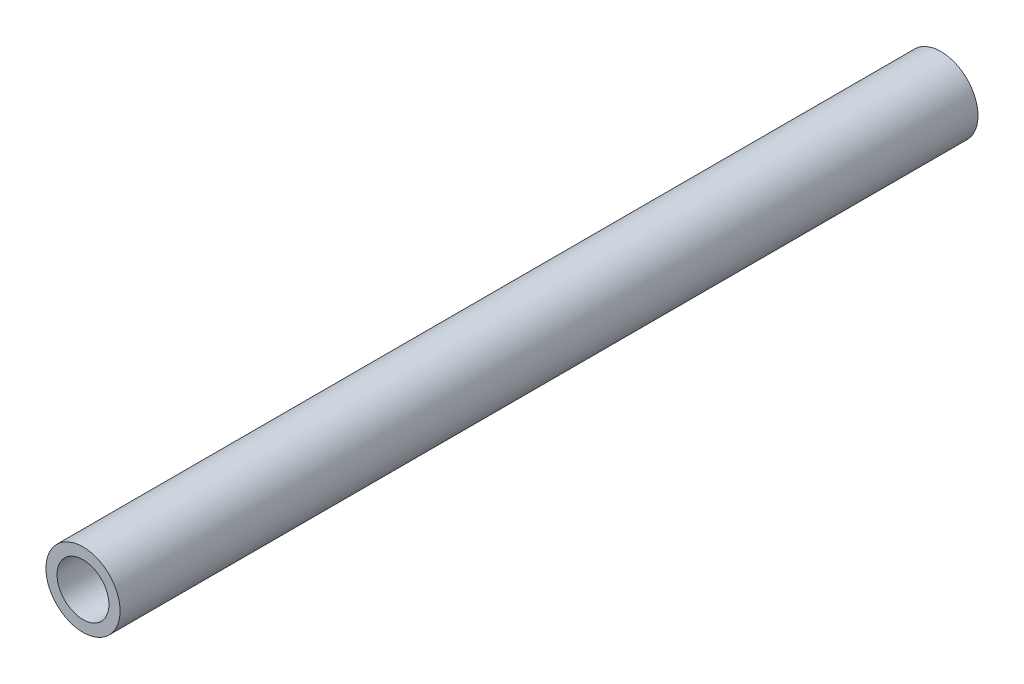
SolidWorks part; units mm, degrees
ref_plane "Front Plane" through (0, 0, 0) normal (0, 0, 1) x (1, 0, 0)
ref_plane "Top Plane" through (0, 0, 0) normal (0, 1, 0) x (1, 0, 0)
ref_plane "Right Plane" through (0, 0, 0) normal (1, 0, 0) x (0, 0, -1)
sketch "Sketch1" plane through (0, 0, 0) normal (0, 0, 1) x (1, 0, 0)
  circle A0 centre (0, 0) radius 12.7
extrude "Boss-Extrude1" add sketch "Sketch1" along normal blind 294
sketch "Sketch2" plane through (0, 0, 294) normal (0, 0, 1) x (1, 0, 0)
  circle A0 centre (0, 0) radius 8.89
extrude "Cut-Extrude1" cut sketch "Sketch2" against normal through all
